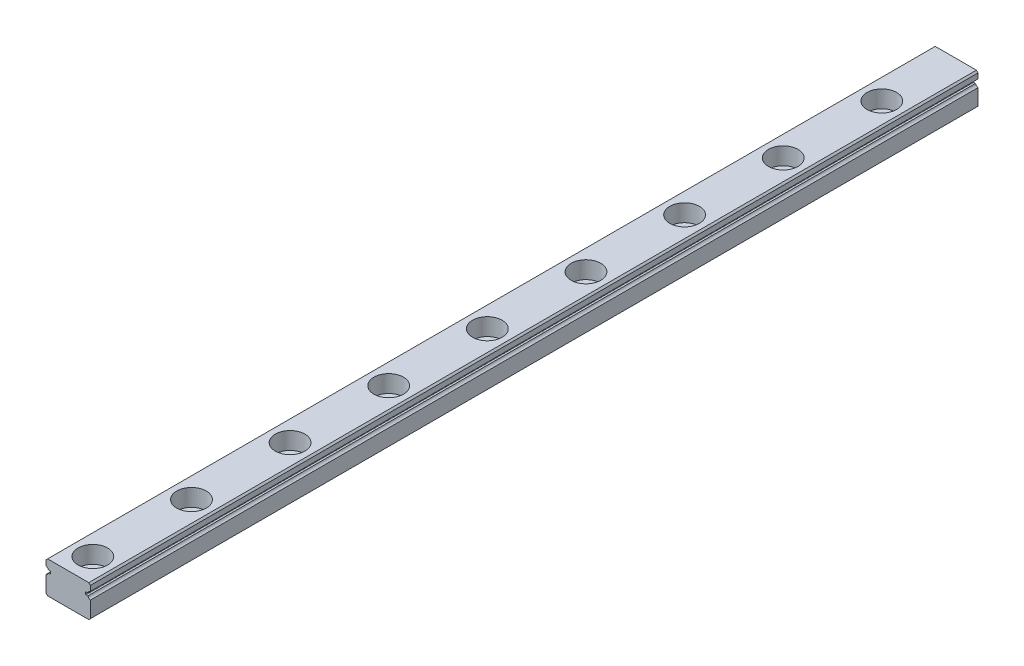
SolidWorks part; units mm, degrees
ref_plane "前视基准面" through (0, 0, 0) normal (0, 0, 1) x (1, 0, 0)
ref_plane "上视基准面" through (0, 0, 0) normal (0, 1, 0) x (1, 0, 0)
ref_plane "右视基准面" through (0, 0, 0) normal (1, 0, 0) x (0, 0, -1)
sketch "草图1" plane through (0, 0, 0) normal (0, 0, 1) x (1, 0, 0)
  line L0 (-1000, 0) -> (0, 0) construction
  line L1 (0, 0) -> (0, 4.2699) construction
  line L15 (-4.5, -2.9053) -> (-4.5, -6.1753)
  line L16 (-4.5, -6.1753) -> (-4.1747, -6.5005)
  line L19 (-4.1747, 0) -> (-4.5, -0.3253)
  line L20 (-4.5, -0.3253) -> (-4.5, -1.3953)
  line L23 (-3.5401, -1.9703) -> (-3.5401, -2.3303)
  line L27 (-4.1747, -6.5005) -> (0, -6.5005)
  line L37 (-3.6301, -1.8803) -> (-3.9901, -1.8803)
  line L38 (-3.6301, -2.4203) -> (-3.9901, -2.4203)
  line L40 (-4.1747, 0) -> (0, 0)
  line L41 (4.1747, 0) -> (0, 0)
  line L42 (3.6301, -2.4203) -> (3.9901, -2.4203)
  line L43 (3.6301, -1.8803) -> (3.9901, -1.8803)
  line L44 (4.1747, -6.5005) -> (0, -6.5005)
  line L45 (3.5401, -1.9703) -> (3.5401, -2.3303)
  line L46 (4.5, -0.3253) -> (4.5, -1.3953)
  line L47 (4.1747, 0) -> (4.5, -0.3253)
  line L48 (4.5, -6.1753) -> (4.1747, -6.5005)
  line L49 (4.5, -2.9053) -> (4.5, -6.1753)
  arc A1 (-4.5, -2.9053) -> (-3.9901, -2.4203) centre (-4.7325, -2.1503) ccw
  arc A2 (-3.5401, -1.9703) -> (-3.6301, -1.8803) centre (-3.6301, -1.9703) ccw
  arc A3 (-3.6301, -2.4203) -> (-3.5401, -2.3303) centre (-3.6301, -2.3303) ccw
  arc A4 (3.6301, -2.4203) -> (3.5401, -2.3303) centre (3.6301, -2.3303) cw
  arc A5 (3.5401, -1.9703) -> (3.6301, -1.8803) centre (3.6301, -1.9703) cw
  arc A6 (4.5, -2.9053) -> (3.9901, -2.4203) centre (4.7325, -2.1503) cw
  arc A7 (-3.9901, -1.8803) -> (-4.5, -1.3953) centre (-4.7325, -2.1503) ccw
  arc A8 (3.9901, -1.8803) -> (4.5, -1.3953) centre (4.7325, -2.1503) cw
  point P2 (-3.8101, -1.8803)
  point P16 (-3.8101, -2.4203)
  dimension "D9" = 1.51
  dimension "D10" = 1.58
  dimension "D13" = 0.18
  dimension "D14" = 0.09
  dimension "D6" = 0.09
  dimension "D7" = 0.79
  dimension "D16" = 135
  dimension "D22" = 0.54
  dimension "D2" = 9
  dimension "D3" = 135
  dimension "D4" = 135
  dimension "D5" = 0.46
  dimension "D8" = 1.07
  dimension "D11" = 0.54
  dimension "D12" = 0.27
  dimension "D15" = 0.36
  dimension "D17" = 0.46
  dimension "D18" = 135
  dimension "D19" = 9
  dimension "D20" = 3.27
  dimension "D21" = 0.36
  dimension "D23" = 0.27
extrude "凸台-拉伸1" add sketch "草图1" along normal blind 180
sketch "草图6" plane through (0, 0, 0) normal (0, 1, 0) x (1, 0, 0)
  line L0 (4.1747, -180) -> (-4.1747, -180) construction
  point P0 (0, -175)
  dimension "D1" = 5
hole_wizard "M2 六角头螺栓的柱形沉头孔1" positions "草图6" profile "草图4" counterbore size "M2" standard "GB" end condition up to next
sketch "草图4" plane through (0, 0, 175) normal (1, 0, 0) x (0, 0, 1)
  line L0 (0, 0) -> (0, 6.5005)
  line L1 (0, 6.5005) -> (1.2, 6.5005)
  line L3 (1.2, 6.5005) -> (1.2, 3.5)
  line L4 (1.2, 3.5) -> (3, 3.5)
  line L5 (3, 3.5) -> (3, 0)
  line L7 (3, 0) -> (0, 0)
  line L11 (0, -6.35) -> (0, 107.95) construction
  dimension "通孔孔直径" = 2.4
  dimension "通孔孔深度" = 6.5005
  dimension "柱形沉头孔直径" = 6
  dimension "柱形沉头孔深度" = 3.5
pattern_linear "阵列(线性)1" count 1 spacing 50 along (0, 0, -1) count 9 spacing 20 along (0, 0, -1) of "M2 六角头螺栓的柱形沉头孔1"
